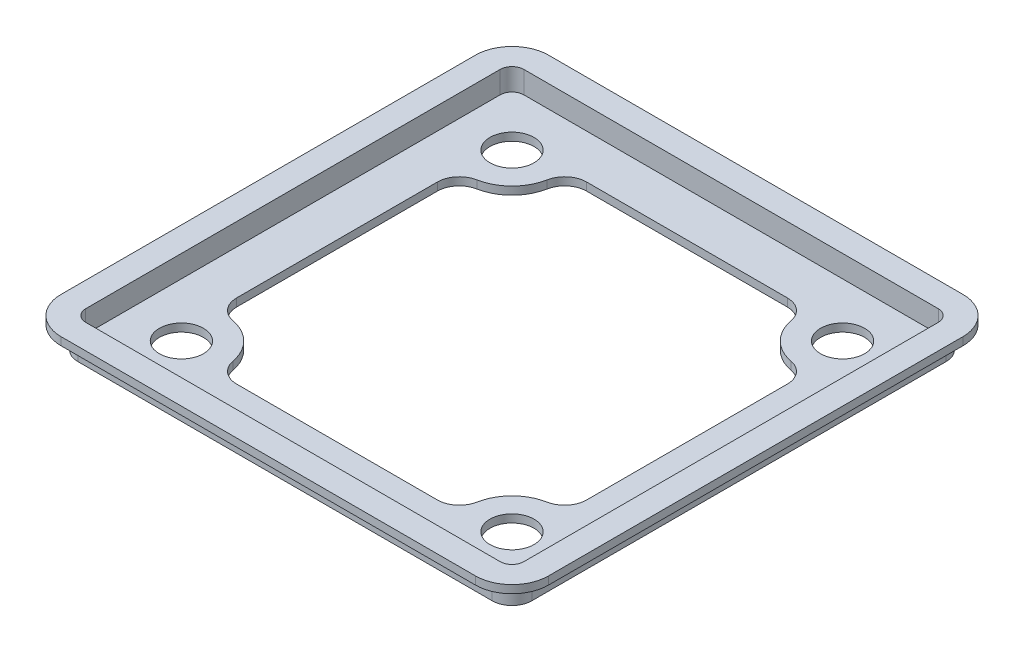
SolidWorks part; units mm, degrees
ref_plane "前基準面" through (0, 0, 0) normal (0, 0, 1) x (1, 0, 0)
ref_plane "上基準面" through (0, 0, 0) normal (0, 1, 0) x (1, 0, 0)
ref_plane "右基準面" through (0, 0, 0) normal (1, 0, 0) x (0, 0, -1)
sketch "Sketch1" plane through (0, 0, 0) normal (0, 1, 0) x (1, 0, 0)
  line L5 (-51.5, -51.5) -> (51.5, -51.5)
  line L6 (-51.5, -51.5) -> (-51.5, 51.5)
  line L7 (-51.5, 51.5) -> (51.5, 51.5)
  line L8 (51.5, -51.5) -> (51.5, 51.5)
  line L9 (0, 51.5) -> (0, -51.5) construction
  line L10 (-51.5, 0) -> (51.5, 0) construction
  circle A0 centre (-37.5, 37.5) radius 5
  circle A1 centre (37.5, 37.5) radius 5
  circle A2 centre (37.5, -37.5) radius 5
  circle A3 centre (-37.5, -37.5) radius 5
  point P0 (0, 0)
  dimension "D2" = 75
  dimension "D3" = 75
  dimension "D4" = 10
  dimension "D1" = 103
extrude "Boss-Extrude1" add sketch "Sketch1" along normal blind 1.8
sketch "Sketch2" plane through (0, 0, 0) normal (0, -1, 0) x (1, 0, 0)
  line L0 (-49.7, 49.7) -> (-49.7, -49.7)
  line L1 (-49.7, -49.7) -> (49.7, -49.7)
  line L2 (49.7, -49.7) -> (49.7, 49.7)
  line L3 (49.7, 49.7) -> (-49.7, 49.7)
  line L4 (51.5, -51.5) -> (51.5, 51.5)
  line L5 (51.5, 51.5) -> (-51.5, 51.5)
  line L6 (-51.5, 51.5) -> (-51.5, -51.5)
  line L7 (-51.5, -51.5) -> (51.5, -51.5)
  line L8 (51.5, -51.5) -> (51.5, 51.5)
  line L9 (51.5, 51.5) -> (-51.5, 51.5)
  line L10 (-51.5, 51.5) -> (-51.5, -51.5)
  line L11 (-51.5, -51.5) -> (51.5, -51.5)
  dimension "D1" = 0
  dimension "D2" = 1.8
extrude "Boss-Extrude2" add sketch "Sketch2" against normal offset from surface (6.8 mm away) 5 up to face at (0, 1.8, 0) offset beyond the face yes
fillet "Fillet1" radius 4.5 4 edges at (-51.5, 3.4, -51.5) (51.5, 3.4, -51.5) (51.5, 3.4, 51.5) (-51.5, 3.4, 51.5)
sketch "Sketch3" plane through (0, 6.8, 0) normal (0, 1, 0) x (1, 0, 0)
  line L5 (-49.7, 49.7) -> (-49.7, -49.7)
  line L6 (49.7, 49.7) -> (-49.7, 49.7)
  line L7 (49.7, -49.7) -> (49.7, 49.7)
  line L8 (-49.7, -49.7) -> (49.7, -49.7)
  line L9 (-49.7, 49.7) -> (-49.7, -49.7)
  line L10 (49.7, 49.7) -> (-49.7, 49.7)
  line L11 (49.7, -49.7) -> (49.7, 49.7)
  line L12 (-49.7, -49.7) -> (49.7, -49.7)
  line L18 (47, 55.3) -> (-47, 55.3)
  line L19 (-55.3, 47) -> (-55.3, -47)
  line L20 (-47, -55.3) -> (47, -55.3)
  line L21 (55.3, -47) -> (55.3, 47)
  line L22 (47, 55.3) -> (-47, 55.3)
  line L23 (-55.3, 47) -> (-55.3, -47)
  line L24 (-47, -55.3) -> (47, -55.3)
  line L25 (55.3, -47) -> (55.3, 47)
  arc A8 (-47, 55.3) -> (-55.3, 47) centre (-47, 47) ccw
  arc A9 (-55.3, -47) -> (-47, -55.3) centre (-47, -47) ccw
  arc A10 (47, -55.3) -> (55.3, -47) centre (47, -47) ccw
  arc A11 (55.3, 47) -> (47, 55.3) centre (47, 47) ccw
  arc A12 (-47, 55.3) -> (-55.3, 47) centre (-47, 47) ccw
  arc A13 (-55.3, -47) -> (-47, -55.3) centre (-47, -47) ccw
  arc A14 (47, -55.3) -> (55.3, -47) centre (47, -47) ccw
  arc A15 (55.3, 47) -> (47, 55.3) centre (47, 47) ccw
  dimension "D3" = 110.6
  dimension "D1" = 0
  dimension "D2" = 3.8
extrude "Boss-Extrude3" add sketch "Sketch3" against normal blind 1.8
sketch "Sketch4" plane through (0, 1.8, 0) normal (0, 1, 0) x (1, 0, 0)
  line L0 (0, 0) -> (55.3, 0) construction
  line L1 (55.3, -47) -> (55.3, 47) construction
  circle A0 centre (-22.6, 35) radius 3
  circle A1 centre (0, 35) radius 3
  circle A2 centre (22.6, 35) radius 3
  circle A3 centre (0, -35) radius 3
  circle A4 centre (22.6, -35) radius 3
  circle A5 centre (-22.6, -35) radius 3
  dimension "D3" = 22.6
  dimension "D4" = 70
  dimension "D5" = 6
  dimension "D1" = 3
  dimension "D2" = 2
extrude "Cut-Extrude1" [suppressed] cut sketch "Sketch4" against normal through all
fillet "Fillet3" radius 2.7 4 edges at (49.7, 4.3, 49.7) (49.7, 4.3, -49.7) (-49.7, 4.3, -49.7) (-49.7, 4.3, 49.7)
sketch "Sketch5" plane through (0, 1.8, 0) normal (0, 1, 0) x (1, 0, 0)
  line L0 (0, 49.7) -> (0, 0) construction
  line L1 (-47, 49.7) -> (47, 49.7) construction
  line L2 (0, 0) -> (49.7, 0) construction
  line L3 (49.7, -47) -> (49.7, 47) construction
  line L4 (22.7637, 39.7) -> (-22.7637, 39.7)
  line L5 (39.7, -22.7637) -> (39.7, 22.7637)
  line L6 (47, 49.7) -> (-47, 49.7) construction
  line L7 (22.7637, -39.7) -> (-22.7637, -39.7)
  line L8 (-39.7, -22.7637) -> (-39.7, 22.7637)
  arc A0 (27.6758, 35.6333) -> (35.6333, 27.6758) centre (37.5, 37.5) ccw
  circle A1 centre (37.5, 37.5) radius 5 construction
  arc A2 (39.7, 22.7637) -> (35.6333, 27.6758) centre (34.7, 22.7637) ccw
  arc A3 (27.6758, 35.6333) -> (22.7637, 39.7) centre (22.7637, 34.7) ccw
  arc A4 (27.6758, -35.6333) -> (22.7637, -39.7) centre (22.7637, -34.7) cw
  arc A5 (39.7, -22.7637) -> (35.6333, -27.6758) centre (34.7, -22.7637) cw
  arc A6 (27.6758, -35.6333) -> (35.6333, -27.6758) centre (37.5, -37.5) cw
  arc A7 (-39.7, -22.7637) -> (-35.6333, -27.6758) centre (-34.7, -22.7637) ccw
  arc A8 (-27.6758, -35.6333) -> (-35.6333, -27.6758) centre (-37.5, -37.5) ccw
  arc A9 (-27.6758, -35.6333) -> (-22.7637, -39.7) centre (-22.7637, -34.7) ccw
  arc A10 (-27.6758, 35.6333) -> (-22.7637, 39.7) centre (-22.7637, 34.7) cw
  arc A11 (-39.7, 22.7637) -> (-35.6333, 27.6758) centre (-34.7, 22.7637) cw
  arc A12 (-27.6758, 35.6333) -> (-35.6333, 27.6758) centre (-37.5, 37.5) cw
  point P30 (39.7, 0)
  point P37 (0, -39.7)
  point P44 (0, 39.7)
  dimension "D3" = 5
  dimension "D4" = 5
  dimension "D1" = 10
  dimension "D2" = 10
extrude "Cut-Extrude2" cut sketch "Sketch5" against normal through all
